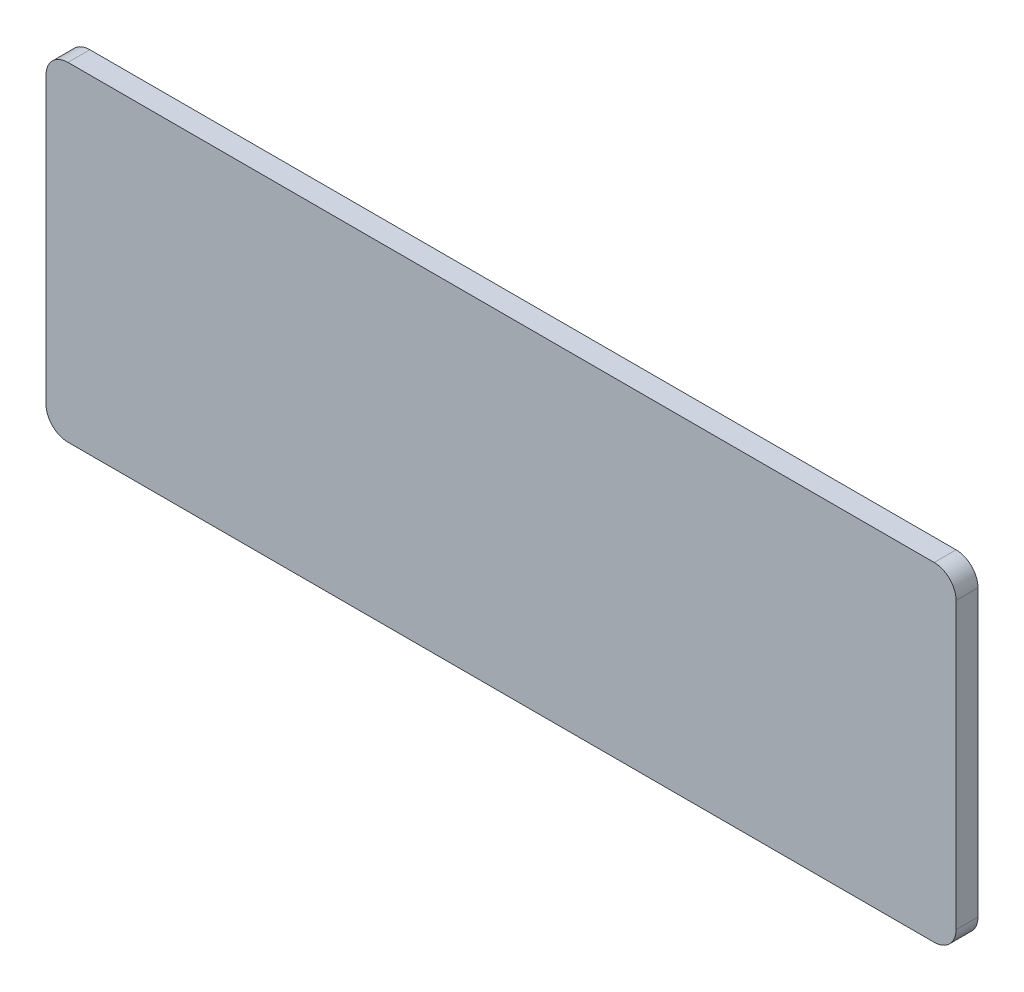
SolidWorks part; units mm, degrees
ref_plane "Front Plane" through (0, 0, 0) normal (0, 0, 1) x (1, 0, 0)
ref_plane "Top Plane" through (0, 0, 0) normal (0, 1, 0) x (1, 0, 0)
ref_plane "Right Plane" through (0, 0, 0) normal (1, 0, 0) x (0, 0, -1)
sketch "Sketch1" plane through (0, 0, 0) normal (0, 0, 1) x (1, 0, 0)
  line L1 (205, 60) -> (-190, 60)
  line L2 (215, 50) -> (215, -80)
  line L3 (205, -90) -> (-190, -90)
  line L4 (-200, 50) -> (-200, -80)
  arc A0 (205, 60) -> (215, 50) centre (205, 50) cw
  arc A1 (215, -80) -> (205, -90) centre (205, -80) cw
  arc A2 (-190, -90) -> (-200, -80) centre (-190, -80) cw
  arc A3 (-190, 60) -> (-200, 50) centre (-190, 50) ccw
  point P0 (0, 0)
  point P10 (215, -90)
  point P13 (-200, -90)
  point P16 (-200, 60)
  dimension "D3" = 10
  dimension "D1" = 415
  dimension "D2" = 150
extrude "Boss-Extrude1" add sketch "Sketch1" along normal blind 10
